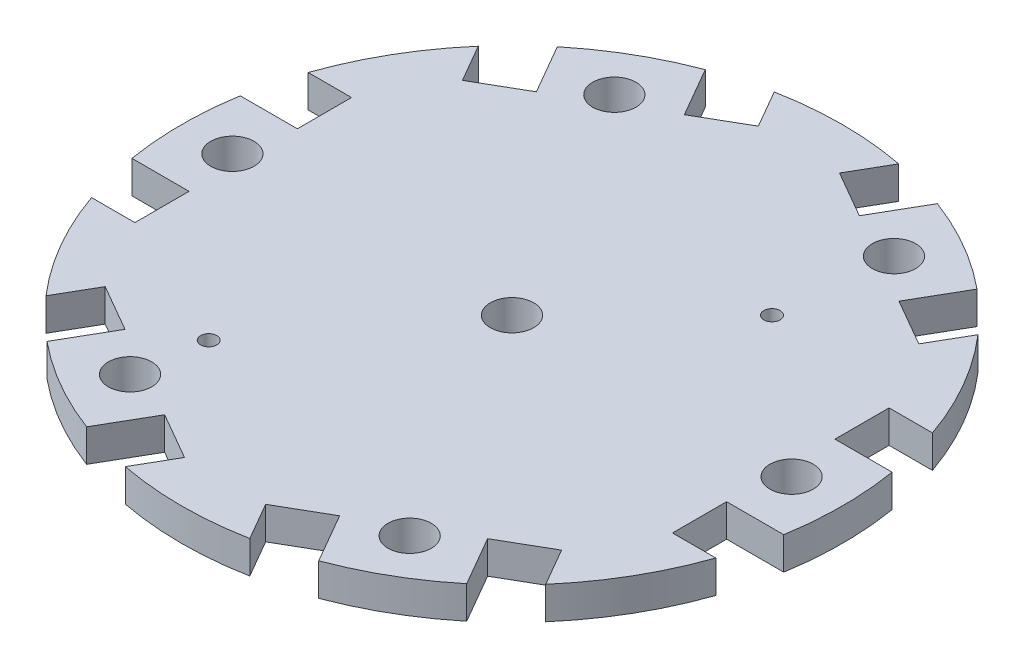
SolidWorks part; units mm, degrees
ref_plane "Alzado" through (0, 0, 0) normal (0, 0, 1) x (1, 0, 0)
ref_plane "Planta" through (0, 0, 0) normal (0, 1, 0) x (1, 0, 0)
ref_plane "Vista lateral" through (0, 0, 0) normal (1, 0, 0) x (0, 0, -1)
sketch "Croquis1" plane through (0, 0, 0) normal (0, 1, 0) x (1, 0, 0)
  circle A0 centre (0, 0) radius 30.5
extrude "Saliente-Extruir1" add sketch "Croquis1" along normal blind 3
sketch "Croquis2" plane through (0, 3, 0) normal (0, 1, 0) x (1, 0, 0)
  circle A0 centre (0, 0) radius 2
extrude "Cortar-Extruir1" cut sketch "Croquis2" against normal blind 4
sketch "Croquis5" plane through (0, 3, 0) normal (0, 1, 0) x (1, 0, 0)
  line L1 (28.8141, -5) -> (30.0874, -5)
  line L2 (28.8141, 5) -> (30.0874, 5)
  line L3 (-24.8141, 10) -> (-28.8141, 10)
  line L4 (24.8141, -5) -> (24.8141, -10)
  line L5 (-24.8141, -10) -> (-28.8141, -10)
  line L6 (24.8141, -5) -> (28.8141, -5)
  line L7 (24.8141, 5) -> (24.8141, 10)
  line L8 (-24.8141, 5) -> (-28.8141, 5)
  line L9 (-24.8141, 5) -> (-24.8141, 10)
  line L10 (-24.8141, -5) -> (-28.8141, -5)
  line L11 (-24.8141, -5) -> (-24.8141, -10)
  line L12 (24.8141, 5) -> (28.8141, 5)
  line L13 (24.8141, -10) -> (28.8141, -10)
  line L14 (24.8141, 10) -> (28.8141, 10)
  line L15 (-28.8141, 5) -> (-30.0874, 5)
  line L16 (-28.8141, -5) -> (-30.0874, -5)
  line L17 (18.7372, 22.4537) -> (19.3738, 23.5564)
  line L18 (-24.8141, 0) -> (-12.407, -21.4896)
  line L19 (-12.407, -21.4896) -> (12.407, -21.4896)
  line L20 (12.407, -21.4896) -> (24.8141, 0)
  line L21 (24.8141, 0) -> (12.407, 21.4896)
  line L22 (12.407, 21.4896) -> (-12.407, 21.4896)
  line L23 (-12.407, 21.4896) -> (-24.8141, 0)
  line L24 (-21.0673, -16.4896) -> (-23.0673, -19.9537)
  line L25 (-3.7468, -26.4896) -> (-5.7468, -29.9537)
  line L26 (-16.7372, -18.9896) -> (-18.7372, -22.4537)
  line L27 (-16.7372, -18.9896) -> (-21.0673, -16.4896)
  line L28 (-8.0769, -23.9896) -> (-10.0769, -27.4537)
  line L29 (-8.0769, -23.9896) -> (-3.7468, -26.4896)
  line L30 (-18.7372, -22.4537) -> (-19.3738, -23.5564)
  line L31 (-10.0769, -27.4537) -> (-10.7136, -28.5564)
  line L32 (10.0769, 27.4537) -> (10.7136, 28.5564)
  line L33 (16.7372, 18.9896) -> (21.0673, 16.4896)
  line L34 (16.7372, 18.9896) -> (18.7372, 22.4537)
  line L35 (8.0769, 23.9896) -> (3.7468, 26.4896)
  line L36 (8.0769, 23.9896) -> (10.0769, 27.4537)
  line L37 (21.0673, 16.4896) -> (23.0673, 19.9537)
  line L38 (3.7468, 26.4896) -> (5.7468, 29.9537)
  line L39 (-3.7468, 26.4896) -> (-5.7468, 29.9537)
  line L40 (-21.0673, 16.4896) -> (-23.0673, 19.9537)
  line L41 (-8.0769, 23.9896) -> (-10.0769, 27.4537)
  line L42 (-8.0769, 23.9896) -> (-3.7468, 26.4896)
  line L43 (-16.7372, 18.9896) -> (-18.7372, 22.4537)
  line L44 (-16.7372, 18.9896) -> (-21.0673, 16.4896)
  line L45 (-10.0769, 27.4537) -> (-10.7136, 28.5564)
  line L46 (-18.7372, 22.4537) -> (-19.3738, 23.5564)
  line L47 (10.0769, -27.4537) -> (10.7136, -28.5564)
  line L48 (18.7372, -22.4537) -> (19.3738, -23.5564)
  line L49 (8.0769, -23.9896) -> (3.7468, -26.4896)
  line L50 (8.0769, -23.9896) -> (10.0769, -27.4537)
  line L51 (16.7372, -18.9896) -> (21.0673, -16.4896)
  line L52 (16.7372, -18.9896) -> (18.7372, -22.4537)
  line L53 (3.7468, -26.4896) -> (5.7468, -29.9537)
  line L54 (21.0673, -16.4896) -> (23.0673, -19.9537)
  circle A0 centre (0, 0) radius 21.4896 construction
  circle A1 centre (0, 0) radius 30.5 construction
  arc A2 (-28.8141, 10) -> (-30.0874, 5) centre (0, 0) ccw
  arc A3 (-5.7468, 29.9537) -> (-10.7136, 28.5564) centre (0, 0) ccw
  arc A4 (-30.0874, -5) -> (-28.8141, -10) centre (0, 0) ccw
  arc A5 (30.0874, -5) -> (28.8141, -10) centre (0, 0) cw
  arc A6 (28.8141, 10) -> (30.0874, 5) centre (0, 0) cw
  arc A7 (-23.0673, -19.9537) -> (-19.3738, -23.5564) centre (0, 0) ccw
  arc A8 (-10.7136, -28.5564) -> (-5.7468, -29.9537) centre (0, 0) ccw
  arc A9 (-19.3738, 23.5564) -> (-23.0673, 19.9537) centre (0, 0) ccw
  arc A10 (19.3738, 23.5564) -> (23.0673, 19.9537) centre (0, 0) cw
  arc A11 (5.7468, 29.9537) -> (10.7136, 28.5564) centre (0, 0) cw
  arc A12 (10.7136, -28.5564) -> (5.7468, -29.9537) centre (0, 0) cw
  arc A13 (23.0673, -19.9537) -> (19.3738, -23.5564) centre (0, 0) cw
  circle M2 centre (0, 0) radius 30.5
extrude "Cortar-Extruir3" cut sketch "Croquis5" against normal blind 4 contours L15 L8 L9 L3 M2 | L14 L7 L12 L2 M2 | L4 L13 L1 L6 M2 | L54 L51 L52 L48 M2 | L49 L53 L47 L50 M2 | L28 L31 L25 L29 M2 | L30 L26 L27 L24 M2 | L10 L16 L5 L11 M2 | L43 L46 L40 L44 M2 | L45 L41 L42 L39 M2 | L38 L35 L36 L32 M2 | L33 L37 L17 L34 M2
sketch "Croquis7" plane through (0, 3, 0) normal (0, 1, 0) x (1, 0, 0)
  line L2 (25.8141, 0) -> (12.907, 22.3556)
  line L3 (12.907, 22.3556) -> (-12.907, 22.3556)
  line L4 (-12.907, 22.3556) -> (-25.8141, 0)
  line L5 (-25.8141, 0) -> (-12.907, -22.3556)
  line L6 (-12.907, -22.3556) -> (12.907, -22.3556)
  line L7 (12.907, -22.3556) -> (25.8141, 0)
  circle A0 centre (25.8141, 0) radius 2
  circle A4 centre (-25.8141, 0) radius 2
  circle A5 centre (0, 0) radius 22.3556 construction
  circle A6 centre (12.907, 22.3556) radius 2
  circle A7 centre (-12.907, -22.3556) radius 2
  circle A8 centre (-12.907, 22.3556) radius 2
  circle A9 centre (12.907, -22.3556) radius 2
extrude "Cortar-Extruir4" cut sketch "Croquis7" against normal blind 10 contours A8 L4 L3 | A4 L4 L5 | A4 L5 L4 | A8 L3 L4 | L2 A6 L3 | L3 A6 L2 | L7 A0 L2 | L2 A0 L7 | A7 L5 L6 | A7 L6 L5 | L6 A9 L7 | L7 A9 L6
sketch "Croquis8" plane through (0, 3, 0) normal (0, 1, 0) x (1, 0, 0)
  line L0 (0, 0) -> (12, 0)
  line L1 (12, 0) -> (12, 12)
  line L2 (0, 0) -> (-12, 0)
  line L3 (-12, 0) -> (-12, -16)
  circle A0 centre (12, 12) radius 0.75
  circle A1 centre (-12, -16) radius 0.75
extrude "Cortar-Extruir5" cut sketch "Croquis8" against normal blind 3
